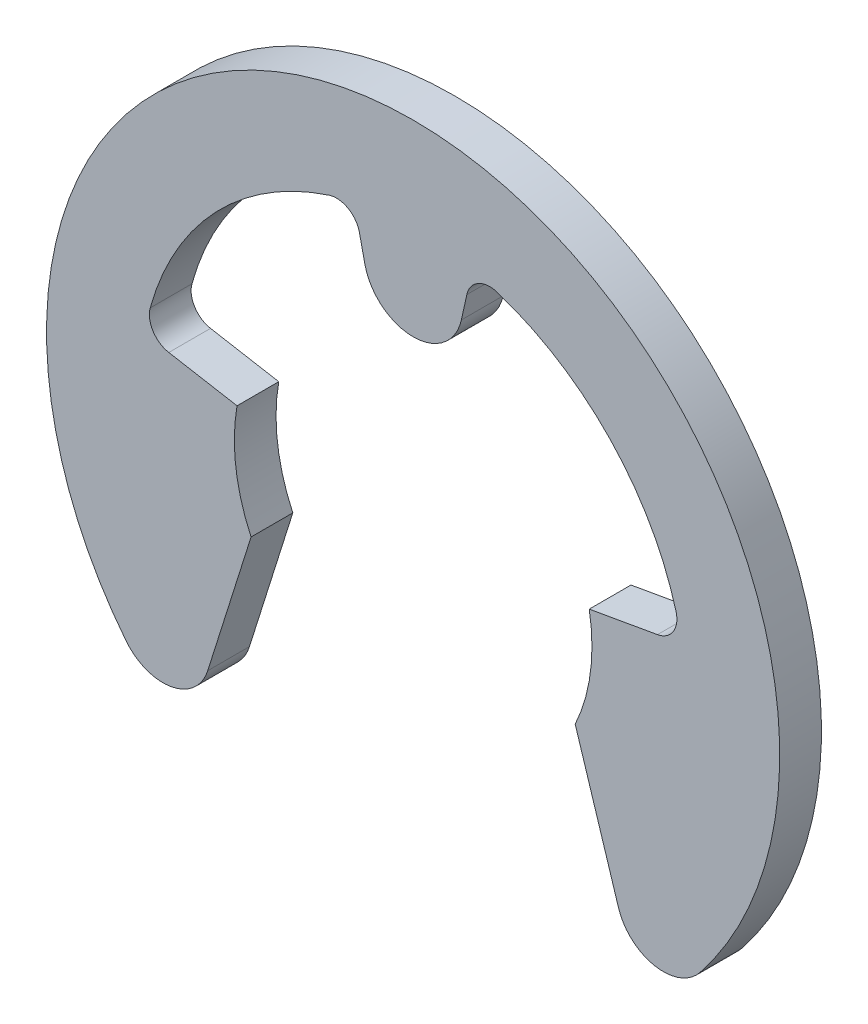
SolidWorks part; units mm, degrees
ref_plane "Plane1" through (0, 0, 0) normal (0, 0, 1) x (1, 0, 0)
ref_plane "Plane2" through (0, 0, 0) normal (0, 1, 0) x (1, 0, 0)
ref_plane "Plane3" through (0, 0, 0) normal (1, 0, 0) x (0, 0, -1)
other "Configuration Table"
sketch "BodySke" plane through (0, 0, 0) normal (0, 0, 1) x (1, 0, 0)
  line L0 (-0.7581, 0) -> (0.7581, 0) construction
  line L1 (0, 0) -> (0, 6.15) construction
  line L2 (0, 0) -> (0.1641, 0.7402) construction
  line L3 (0, 0) -> (5.5738, -2.5991) construction
  line L4 (0, 0) -> (-0.1641, 0.7402) construction
  line L5 (0, 0) -> (-5.5738, -2.5991) construction
  line L6 (2.9544, 0.5209) -> (4.0994, 0.7228)
  line L7 (-2.9544, 0.5209) -> (-4.0994, 0.7228)
  line L8 (0, 0) -> (6.0566, 1.0679) construction
  line L9 (2.7189, -1.2679) -> (3.4462, -3.5744)
  line L10 (-2.7189, -1.2679) -> (-3.4462, -3.5744)
  line L11 (0.809, 3.6493) -> (0.901, 4.064)
  line L12 (-0.809, 3.6493) -> (-0.901, 4.064)
  line L13 (0, 0) -> (-6.0566, 1.0679) construction
  circle A0 centre (0, 0) radius 3 construction
  arc A1 (4.4107, 1.2152) -> (1.4064, 4.3535) centre (0, 0) ccw
  arc A2 (4.8136, -3.8278) -> (-4.8136, -3.8278) centre (0, 0) ccw
  arc A3 (2.7189, -1.2679) -> (2.9544, 0.5209) centre (0, 0) ccw
  arc A4 (-1.4064, 4.3535) -> (-4.4107, 1.2152) centre (0, 0) ccw
  arc A5 (4.0994, 0.7228) -> (4.4107, 1.2152) centre (4.0311, 1.1106) ccw
  arc A7 (1.4064, 4.3535) -> (0.901, 4.064) centre (1.2854, 3.9788) ccw
  arc A8 (-2.9544, 0.5209) -> (-2.7189, -1.2679) centre (0, 0) ccw
  arc A9 (-4.4107, 1.2152) -> (-4.0994, 0.7228) centre (-4.0311, 1.1106) ccw
  arc A10 (-0.809, 3.6493) -> (0.809, 3.6493) centre (0, 3.8287) ccw
  arc A11 (-0.901, 4.064) -> (-1.4064, 4.3535) centre (-1.2854, 3.9788) ccw
  arc A12 (-4.8136, -3.8278) -> (-3.4462, -3.5744) centre (-4.1972, -3.3376) ccw
  arc A13 (3.4462, -3.5744) -> (4.8136, -3.8278) centre (4.1972, -3.3376) ccw
  dimension "OutsideDia" = 12.3
  dimension "CavityDia" = 9.15
  dimension "TipRad" = 0.7875
  dimension "CavityFilletRad" = 0.3938
  dimension "GrooveDia" = 6
  dimension "D3" = 25
  dimension "D4" = 35
  dimension "D1" = 35
  dimension "D2" = 160
extrude "Body" add sketch "BodySke" against normal blind 0.7
equation "' \"Thickness@Body\" = 0.2"
equation "' \"GrooveDia@BodySke\" = 0.8"
equation "' \"OutsideDia@BodySke\" = 2.25"
equation "' \"Thickness@Body\" = 2.5"
equation "' \"GrooveDia@BodySke\" = 30"
equation "' \"OutsideDia@BodySke\" = 52.6"
equation "\"CavityDia@BodySke\" = (\"OutsideDia@BodySke\"  + \"GrooveDia@BodySke\") / 2 "
equation "\"CavityFilletRad@BodySke\" =  (\"CavityDia@BodySke\" - \"GrooveDia@BodySke\") / 2 * 0.25"
equation "\"TipRad@BodySke\" = (\"OutsideDia@BodySke\"  - \"GrooveDia@BodySke\") / 2 * 0.25"
